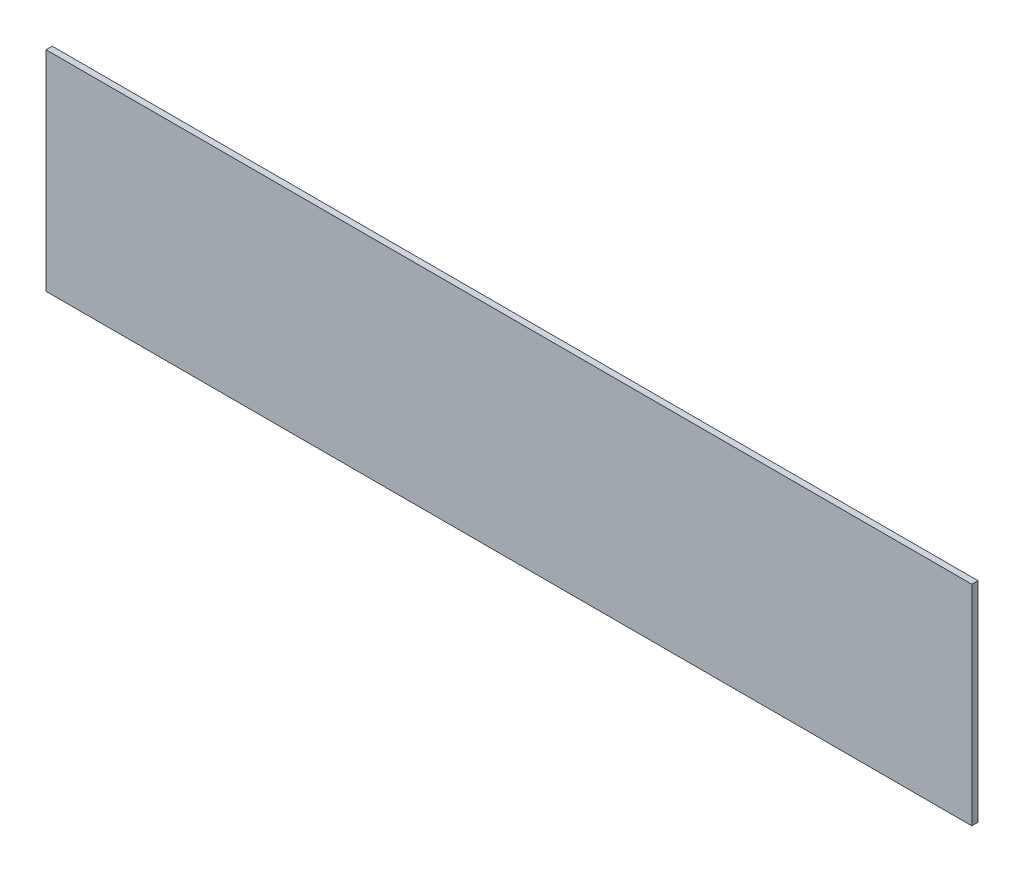
SolidWorks part; units mm, degrees
material "1060 Alloy"
ref_plane "Front" through (0, 0, 0) normal (0, 0, 1) x (1, 0, 0)
ref_plane "Top" through (0, 0, 0) normal (0, 1, 0) x (1, 0, 0)
ref_plane "Right" through (0, 0, 0) normal (1, 0, 0) x (0, 0, -1)
sketch "Sketch1" plane through (0, 0, 0) normal (0, 0, 1) x (1, 0, 0)
  line L1 (-46.6126, -26.6194) -> (143.8874, -26.6194)
  line L2 (-46.6126, -26.6194) -> (-46.6126, 16.4336)
  line L3 (-46.6126, 16.4336) -> (143.8874, 16.4336)
  line L4 (143.8874, -26.6194) -> (143.8874, 16.4336)
  dimension "D1" = 43.053
  dimension "D2" = 190.5
extrude "Boss-Extrude1" add sketch "Sketch1" along normal blind 1.27
